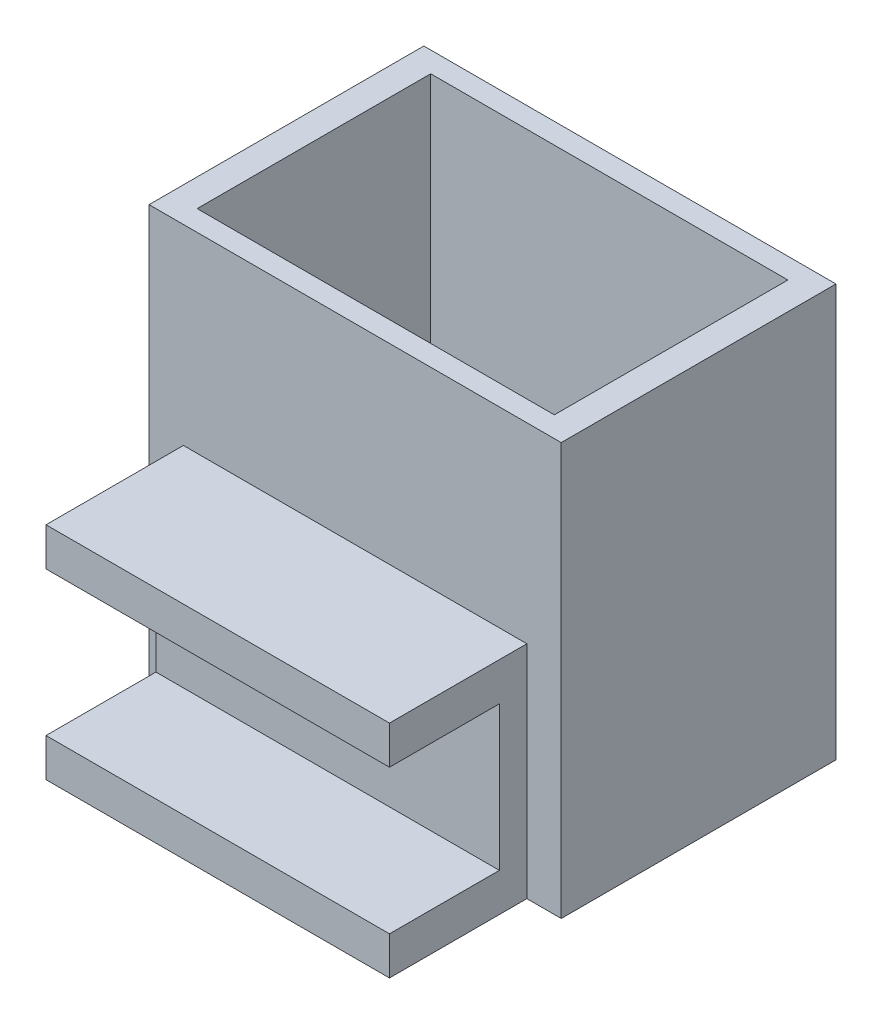
SolidWorks part; units mm, degrees
ref_plane "前视基准面" through (0, 0, 0) normal (0, 0, 1) x (1, 0, 0)
ref_plane "上视基准面" through (0, 0, 0) normal (0, 1, 0) x (1, 0, 0)
ref_plane "右视基准面" through (0, 0, 0) normal (1, 0, 0) x (0, 0, -1)
sketch "草图1" plane through (0, 0, 0) normal (0, 1, 0) x (1, 0, 0)
  line L1 (-15.3715, 12.1835) -> (14.6285, 12.1835)
  line L2 (-15.3715, 12.1835) -> (-15.3715, -7.8165)
  line L3 (-15.3715, -7.8165) -> (14.6285, -7.8165)
  line L4 (14.6285, 12.1835) -> (14.6285, -7.8165)
  dimension "D1" = 30
  dimension "D2" = 20
extrude "凸台-拉伸1" add sketch "草图1" along normal blind 30
sketch "草图2" plane through (0, 30, 0) normal (0, 1, 0) x (1, 0, 0)
  line L0 (-15.3715, 12.1835) -> (-15.3715, -7.8165) construction
  line L1 (-13.3715, 10.6835) -> (12.6285, 10.6835)
  line L2 (-13.3715, 10.6835) -> (-13.3715, -6.3165)
  line L3 (-13.3715, -6.3165) -> (12.6285, -6.3165)
  line L4 (12.6285, 10.6835) -> (12.6285, -6.3165)
  line L5 (14.6285, 12.1835) -> (-15.3715, 12.1835) construction
  dimension "D1" = 26
  dimension "D2" = 17
  dimension "D3" = 2
  dimension "D4" = 1.5
extrude "切除-拉伸2" cut sketch "草图2" against normal blind 25
sketch "草图3" plane through (0, 0, 7.8165) normal (0, 0, 1) x (1, 0, 0)
  line L0 (-12.8715, 16.07) -> (-12.8715, 0)
  line L1 (-15.3715, 0) -> (14.6285, 0) construction
  line L2 (-12.8715, 0) -> (12.1285, 0)
  line L3 (12.1285, 0) -> (12.1285, 16.07)
  line L4 (12.1285, 16.07) -> (-12.8715, 16.07)
  line L6 (14.6285, 30) -> (14.6285, 0) construction
  dimension "D1" = 16.07
  dimension "D2" = 25
  dimension "D3" = 2.5
extrude "凸台-拉伸2" add sketch "草图3" along normal blind 10
sketch "草图4" plane through (12.1285, 0, 0) normal (1, 0, 0) x (0, 0, -1)
  line L0 (-17.8165, 13.285) -> (-9.8165, 13.285)
  line L1 (-17.8165, 0) -> (-17.8165, 16.07) construction
  line L2 (-9.8165, 13.285) -> (-9.8165, 2.785)
  line L3 (-9.8165, 2.785) -> (-17.8165, 2.785)
  line L4 (-17.8165, 2.785) -> (-17.8165, 13.285)
  line L5 (-17.8165, 16.07) -> (-7.8165, 16.07) construction
  dimension "D1" = 10.5
  dimension "D2" = 8
  dimension "D3" = 2.785
extrude "切除-拉伸3" cut sketch "草图4" against normal through all
